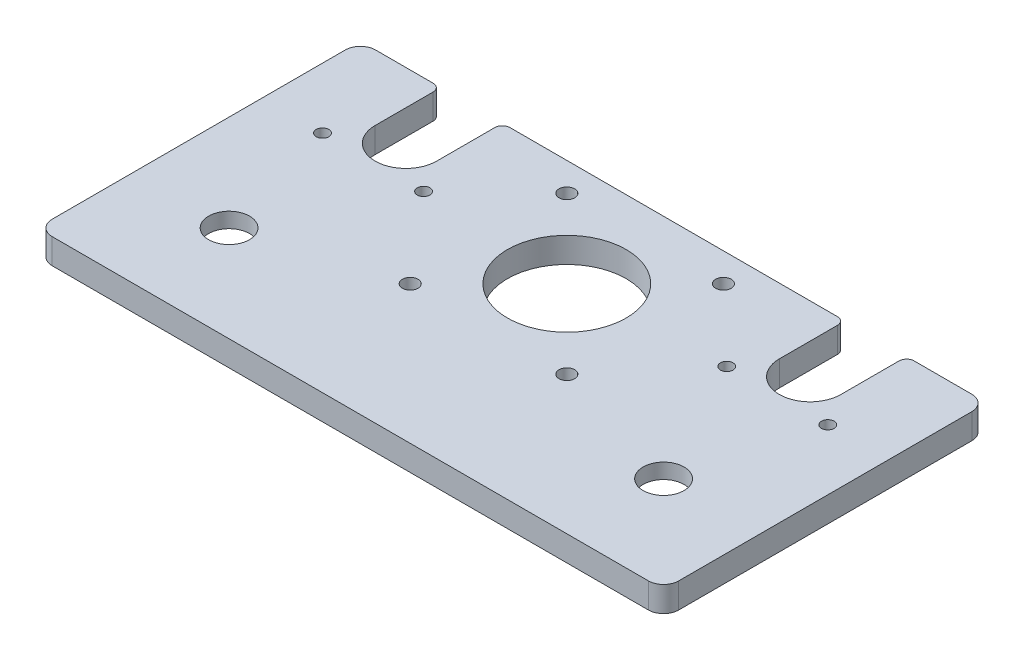
SolidWorks part; units mm, degrees
ref_plane "Front" through (0, 0, 0) normal (0, 0, 1) x (1, 0, 0)
ref_plane "Top" through (0, 0, 0) normal (0, 1, 0) x (1, 0, 0)
ref_plane "Right" through (0, 0, 0) normal (1, 0, 0) x (0, 0, -1)
sketch "Sketch1" plane through (0, 0, 0) normal (0, 1, 0) x (1, 0, 0)
  line L1 (0, 0) -> (124, 0)
  line L2 (0, 0) -> (0, -64)
  line L3 (0, -64) -> (124, -64)
  line L4 (124, 0) -> (124, -64)
  dimension "D1" = 124
  dimension "D2" = 64
extrude "Boss-Extrude1" add sketch "Sketch1" along normal blind 5
sketch "Sketch2" plane through (0, 5, 0) normal (0, 1, 0) x (1, 0, 0)
  line L0 (15.8975, -12.9975) -> (15.8975, 12.3654)
  line L1 (15.8975, 12.3654) -> (28.0975, 12.3654)
  line L2 (28.0975, 12.3654) -> (28.0975, -12.9975)
  line L3 (62, 0) -> (62, -55.3682) construction
  line L4 (124, 0) -> (0, 0) construction
  line L5 (95.9025, 12.3654) -> (95.9025, -12.9975)
  line L6 (108.1025, 12.3654) -> (95.9025, 12.3654)
  line L7 (108.1025, -12.9975) -> (108.1025, 12.3654)
  arc A0 (15.8975, -12.9975) -> (28.0975, -12.9975) centre (21.9975, -12.9975) ccw
  arc A1 (108.1025, -12.9975) -> (95.9025, -12.9975) centre (102.0025, -12.9975) cw
  dimension "D1" = 12.2
extrude "Cut-Extrude1" cut sketch "Sketch2" against normal blind 5
sketch "Sketch3" plane through (0, 0, 0) normal (0, -1, 0) x (1, 0, 0)
  line L0 (3.8975, 60.1) -> (34.1, 60.1)
  line L1 (3.9975, 60) -> (34, 60) construction
  line L2 (3.9975, 60) -> (3.9975, 29.9975) construction
  line L3 (3.9975, 29.9975) -> (34, 29.9975) construction
  line L4 (34, 60) -> (34, 29.9975) construction
  line L5 (90, 60) -> (120.0025, 60) construction
  line L6 (90, 60) -> (90, 29.9975) construction
  line L7 (90, 29.9975) -> (120.0025, 29.9975) construction
  line L8 (120.0025, 60) -> (120.0025, 29.9975) construction
  line L9 (34.1, 60.1) -> (34.1, 29.8975)
  line L10 (3.8975, 29.8975) -> (34.1, 29.8975)
  line L11 (3.8975, 60.1) -> (3.8975, 29.8975)
  line L12 (89.9, 60.1) -> (120.1025, 60.1)
  line L13 (120.1025, 60.1) -> (120.1025, 29.8975)
  line L14 (89.9, 29.8975) -> (120.1025, 29.8975)
  line L15 (89.9, 60.1) -> (89.9, 29.8975)
  dimension "D1" = 0.1
extrude "Cut-Extrude2" cut sketch "Sketch3" against normal blind 2
sketch "Sketch4" plane through (0, 0, 0) normal (0, -1, 0) x (1, 0, 0)
  line L0 (62, 64) -> (62, -12.2198) construction
  line L1 (0, 64) -> (124, 64) construction
  circle A0 centre (34.1, 29.8975) radius 2
  circle A1 centre (34.1, 60.1) radius 2
  circle A2 centre (3.8975, 60.1) radius 2
  circle A3 centre (3.8975, 29.8975) radius 2
  circle A4 centre (120.1025, 29.8975) radius 2
  circle A5 centre (120.1025, 60.1) radius 2
  circle A6 centre (89.9, 60.1) radius 2
  circle A7 centre (89.9, 29.8975) radius 2
  dimension "D1" = 4
extrude "Cut-Extrude3" cut sketch "Sketch4" against normal blind 2
sketch "Sketch5" plane through (0, 0, 0) normal (0, -1, 0) x (1, 0, 0)
  circle A0 centre (18.9987, 44.9987) radius 4.05
  circle A1 centre (105.0013, 44.9987) radius 4.05
  circle A2 centre (77.5, 36.6487) radius 1.55
  circle A3 centre (46.5, 36.6487) radius 1.55
  circle A4 centre (46.5, 5.6487) radius 1.55
  circle A5 centre (77.5, 5.6487) radius 1.55
  circle A6 centre (62, 21.1487) radius 11.75
  dimension "D1" = 8.1
  dimension "D2" = 23.5
  dimension "D3" = 3.1
extrude "Cut-Extrude4" cut sketch "Sketch5" against normal blind 5
sketch "Sketch6" plane through (0, 5, 0) normal (0, 1, 0) x (1, 0, 0)
  circle A0 centre (11.9975, -19.4975) radius 1.25
  circle A1 centre (31.9975, -19.4975) radius 1.25
  circle A2 centre (92.0025, -19.4975) radius 1.25
  circle A3 centre (112.0025, -19.4975) radius 1.25
  dimension "D1" = 2.5
extrude "Cut-Extrude5" cut sketch "Sketch6" against normal blind 10
fillet "Fillet1" radius 3 4 edges at (124, 2.5, 64) (124, 2.5, 0) (0, 2.5, 64) (0, 2.5, 0)
fillet "Fillet2" radius 1.5 4 edges at (95.9025, 2.5, 0) (108.1025, 2.5, 0) (28.0975, 2.5, 0) (15.8975, 2.5, 0)
